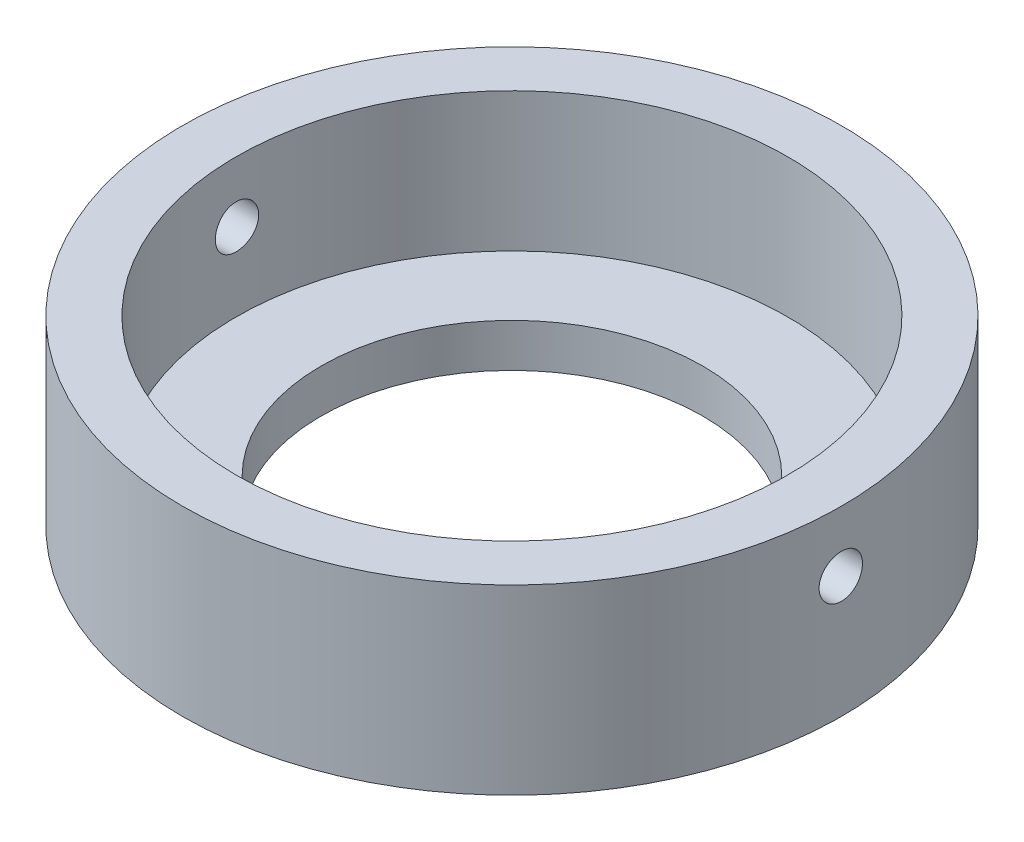
SolidWorks part; units mm, degrees
ref_plane "前视基准面" through (0, 0, 0) normal (0, 0, 1) x (1, 0, 0)
ref_plane "上视基准面" through (0, 0, 0) normal (0, 1, 0) x (1, 0, 0)
ref_plane "右视基准面" through (0, 0, 0) normal (1, 0, 0) x (0, 0, -1)
other "Configuration Table"
sketch "草图1" plane through (0, 0, 0) normal (0, 1, 0) x (1, 0, 0)
  circle A0 centre (0, 0) radius 19
  dimension "D1" = 38
extrude "凸台-拉伸1" add sketch "草图1" along normal blind 2.5
sketch "草图2" plane through (0, 2.5, 0) normal (0, 1, 0) x (1, 0, 0)
  circle A0 centre (0, 0) radius 19
  circle A1 centre (0, 0) radius 15.9
  dimension "D1" = 31.8
extrude "凸台-拉伸2" add sketch "草图2" along normal blind 8
sketch "草图3" plane through (0, 0, 0) normal (0, -1, 0) x (1, 0, 0)
  circle A0 centre (0, 0) radius 11
  dimension "D1" = 22
extrude "切除-拉伸1" cut sketch "草图3" against normal blind 6
sketch "草图4" plane through (0, 10.5, 0) normal (0, 1, 0) x (1, 0, 0)
  line L0 (0, 0) -> (0, 19) construction
  line L1 (0, 0) -> (19, 0) construction
  line L2 (0, 0) -> (-19, 0) construction
  circle A0 centre (0, 0) radius 19 construction
  point P7 (0, 0)
  point P10 (0, 0)
sketch3d "3D草图1"
  point P0 (0, 6.5, -19)
  point P1 (19, 7, 0)
  point P2 (0, 0, 0)
  point P5 (-19, 7, 0)
  point P6 (0, 0, 0)
  point P12 (-18.9995, 8.9237, 0.1398)
  point P16 (-18.9988, 8.1431, 0.2125)
  point P18 (0, 0, 0)
  point P22 (0, 0, 0)
  point P23 (0, 0, 0)
  dimension "D1" = 3.5
  dimension "D2" = 4
  dimension "D3" = 3.5
ref_plane "基准面1" through (-19, 0, 0) normal (-1, 0, 0) x (0, 0, 1)
hole_wizard "M3 螺纹孔1" positions "3D草图5" profile "草图10" tap size "M3" standard "GB"
sketch3d "3D草图5"
  point P0 (19, 7, 0)
  point P4 (-19, 7, 0)
sketch "草图10" plane through (-19, 7, 0) normal (0, 1, 0) x (0, 0, 1)
  line L0 (0, 0) -> (0, 44.6511)
  line L1 (0, 44.6511) -> (1.25, 43.9)
  line L2 (1.25, 43.9) -> (1.25, 0.275)
  line L3 (1.25, 0.275) -> (1.525, 0)
  line L5 (1.525, 0) -> (0, 0)
  line L6 (-1.25, 0.275) -> (-1.525, 0) construction
  line L10 (0, 44.6511) -> (-1.25, 43.9) construction
  line L11 (0, -6.35) -> (0, 107.95) construction
  dimension "螺纹孔钻头直径" = 2.5
  dimension "螺纹孔钻头深度" = 43.9
  dimension "近端锥形沉头孔直径" = 3.05
  dimension "近端锥形沉头孔角度" = 90
  dimension "导头角度" = 118
cosmetic thread "孔螺纹线3" parameters "D1"=42.4, "D2"=3
